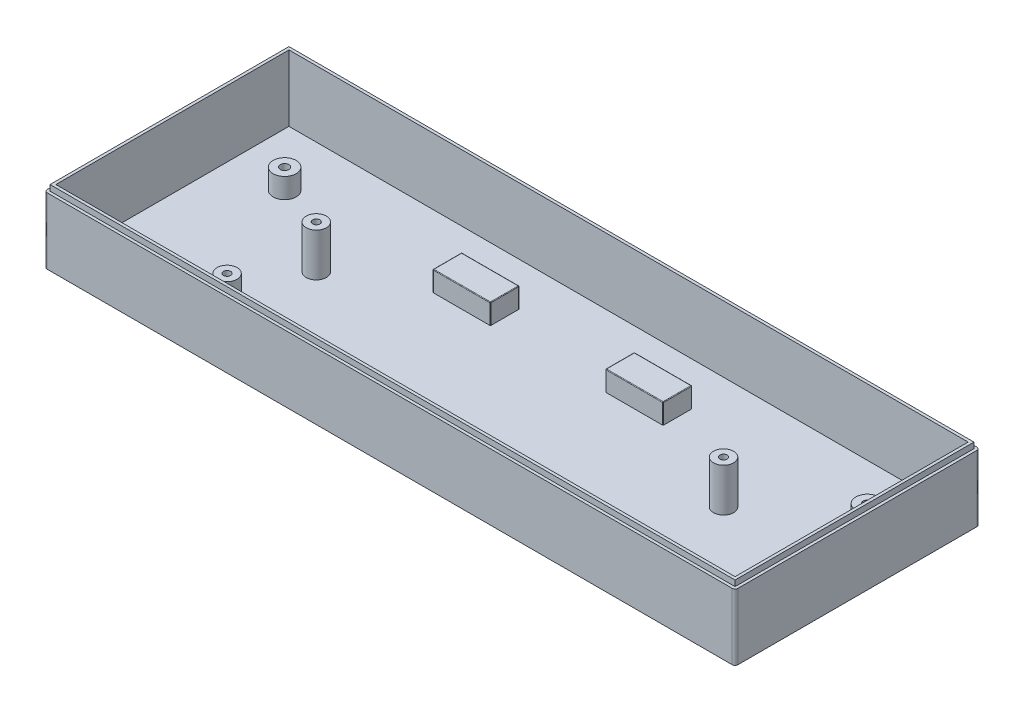
SolidWorks part; units mm, degrees
ref_plane "Front Plane" through (0, 0, 0) normal (0, 0, 1) x (1, 0, 0)
ref_plane "Top Plane" through (0, 0, 0) normal (0, 1, 0) x (1, 0, 0)
ref_plane "Right Plane" through (0, 0, 0) normal (1, 0, 0) x (0, 0, -1)
sketch "Sketch1" plane through (0, 0, 0) normal (0, 1, 0) x (1, 0, 0)
  line L1 (-120, 42.5) -> (120, 42.5)
  line L2 (-120, 42.5) -> (-120, -42.5)
  line L3 (-120, -42.5) -> (120, -42.5)
  line L4 (120, 42.5) -> (120, -42.5)
  line L5 (-120, 42.5) -> (120, -42.5) construction
  line L6 (-120, -42.5) -> (120, 42.5) construction
  point P0 (0, 0)
  dimension "D1" = 240
  dimension "D2" = 85
extrude "Boss-Extrude1" add sketch "Sketch1" along normal blind 25
sketch "Sketch2" plane through (0, 25, 0) normal (0, 1, 0) x (1, 0, 0)
  line L8 (118, -40.5) -> (118, 40.5)
  line L9 (118, 40.5) -> (-118, 40.5)
  line L10 (-118, 40.5) -> (-118, -40.5)
  line L11 (-118, -40.5) -> (118, -40.5)
  line L12 (118, -40.5) -> (118, 40.5)
  line L13 (118, 40.5) -> (-118, 40.5)
  line L14 (-118, 40.5) -> (-118, -40.5)
  line L15 (-118, -40.5) -> (118, -40.5)
  dimension "D1" = 2
extrude "Cut-Extrude1" cut sketch "Sketch2" against normal blind 23
sketch "Sketch3" plane through (0, 25, 0) normal (0, 1, 0) x (1, 0, 0)
  line L10 (120, 42.5) -> (-120, 42.5) construction
  line L11 (120, -42.5) -> (120, 42.5) construction
  line L12 (-120, -42.5) -> (120, -42.5) construction
  line L13 (-120, 42.5) -> (-120, -42.5) construction
  line L14 (119, -41.5) -> (119, 41.5)
  line L15 (-119, -41.5) -> (119, -41.5)
  line L16 (119, 41.5) -> (-119, 41.5)
  line L17 (-119, 41.5) -> (-119, -41.5)
  line L18 (119, -41.5) -> (119, 41.5)
  line L19 (-119, -41.5) -> (119, -41.5)
  line L20 (119, 41.5) -> (-119, 41.5)
  line L21 (-119, 41.5) -> (-119, -41.5)
  line L22 (120, -42.5) -> (120, 42.5)
  line L23 (-120, -42.5) -> (120, -42.5)
  line L24 (-120, 42.5) -> (-120, -42.5)
  line L25 (120, 42.5) -> (-120, 42.5)
  dimension "D1" = 1
extrude "Cut-Extrude2" cut sketch "Sketch3" against normal blind 2
sketch "Sketch5" plane through (0, 2, 0) normal (0, 1, 0) x (1, 0, 0)
  line L0 (-118, 20.5) -> (118, 20.5) construction
  line L1 (-118, 40.5) -> (-118, -40.5) construction
  line L2 (118, -40.5) -> (118, 40.5) construction
  line L6 (118, 40.5) -> (-118, 40.5) construction
  line L8 (-118, 40.5) -> (-118, -40.5) construction
  line L9 (-43, 25.5) -> (-23, 25.5)
  line L10 (-43, 25.5) -> (-43, 15.5)
  line L11 (-43, 15.5) -> (-23, 15.5)
  line L12 (-23, 25.5) -> (-23, 15.5)
  line L13 (-43, 25.5) -> (-23, 15.5) construction
  line L14 (-43, 15.5) -> (-23, 25.5) construction
  line L15 (17, 25.5) -> (37, 25.5)
  line L16 (17, 25.5) -> (17, 15.5)
  line L17 (17, 15.5) -> (37, 15.5)
  line L18 (37, 25.5) -> (37, 15.5)
  line L19 (17, 25.5) -> (37, 15.5) construction
  line L20 (17, 15.5) -> (37, 25.5) construction
  line L22 (-112.5, 30.5) -> (112.5, 30.5) construction
  line L23 (-112.5, 30.5) -> (-112.5, 10.5) construction
  line L24 (-112.5, 10.5) -> (112.5, 10.5) construction
  line L25 (112.5, 30.5) -> (112.5, 10.5) construction
  line L26 (-112.5, 30.5) -> (112.5, 10.5) construction
  line L27 (-112.5, 10.5) -> (112.5, 30.5) construction
  circle A0 centre (-99.5, 20.5) radius 4
  circle A1 centre (103, 20.5) radius 4
  point P12 (-33, 20.5)
  point P17 (27, 20.5)
  point P24 (0, 20.5)
  dimension "D1" = 202.5
  dimension "D2" = 18.5
  dimension "D3" = 8
  dimension "D4" = 8
  dimension "D6" = 85
  dimension "D5" = 20
  dimension "D7" = 145
  dimension "D8" = 10
  dimension "D9" = 20
  dimension "D10" = 20
  dimension "D11" = 225
  dimension "D12" = 5.5
  dimension "D13" = 10
extrude "Boss-Extrude2" add sketch "Sketch5" along normal blind 7
sketch "Sketch6" plane through (0, 9, 0) normal (0, 1, 0) x (1, 0, 0)
  circle A0 centre (-99.5, 20.5) radius 1.5
  circle A1 centre (103, 20.5) radius 1.5
  dimension "D1" = 3
  dimension "D2" = 3
extrude "Cut-Extrude3" cut sketch "Sketch6" against normal blind 5
sketch "Sketch7" plane through (0, 2, 0) normal (0, 1, 0) x (1, 0, 0)
  line L0 (-118, 40.5) -> (-118, -40.5) construction
  line L1 (-72.5, 3.5) -> (75, 3.5) construction
  line L2 (-72.5, 3.5) -> (-72.5, -31.5) construction
  line L3 (-72.5, -31.5) -> (75, -31.5) construction
  line L4 (75, 3.5) -> (75, -31.5) construction
  line L7 (-118, -40.5) -> (118, -40.5) construction
  circle A0 centre (72, 1.5) radius 3.5
  circle A1 centre (72, -29.5) radius 3.5 construction
  circle A2 centre (-69.5, -29.5) radius 3.5
  circle A3 centre (72, -29.5) radius 1.5 construction
  circle A4 centre (72, 1.5) radius 1.5 construction
  circle A5 centre (-69.5, 1.5) radius 3.5
  dimension "D5" = 7
  dimension "D6" = 7
  dimension "D7" = 7
  dimension "D8" = 31
  dimension "D9" = 3
  dimension "D10" = 3
  dimension "D11" = 2
  dimension "D12" = 3
  dimension "D13" = 3
  dimension "D14" = 7
  dimension "D1" = 45.5
  dimension "D2" = 147.5
  dimension "D3" = 35
  dimension "D4" = 9
extrude "Boss-Extrude3" add sketch "Sketch7" along normal blind 15
sketch "Sketch8" plane through (0, 17, 0) normal (0, 1, 0) x (1, 0, 0)
  circle A0 centre (72, 1.5) radius 1.25
  circle A1 centre (-69.5, -29.5) radius 1.25
  circle A2 centre (-69.5, 1.5) radius 1.25
  dimension "D1" = 2.5
  dimension "D2" = 2.5
  dimension "D3" = 2.5
extrude "Cut-Extrude4" cut sketch "Sketch8" against normal blind 7
fillet "Fillet1" radius 0.2 16 edges at (37, 9, -20.5) (27, 9, -15.5) (17, 9, -20.5) (27, 9, -25.5) (-33, 9, -15.5) (-33, 9, -25.5) (-23, 9, -20.5) (-43, 9, -20.5) (17, 5.5, -15.5) (17, 5.5, -25.5) (37, 5.5, -15.5) (37, 5.5, -25.5) (-23, 5.5, -25.5) (-43, 5.5, -25.5) (-23, 5.5, -15.5) (-43, 5.5, -15.5)
fillet "Fillet2" radius 1 4 edges at (120, 11.5, -42.5) (120, 11.5, 42.5) (-120, 11.5, -42.5) (-120, 11.5, 42.5)
